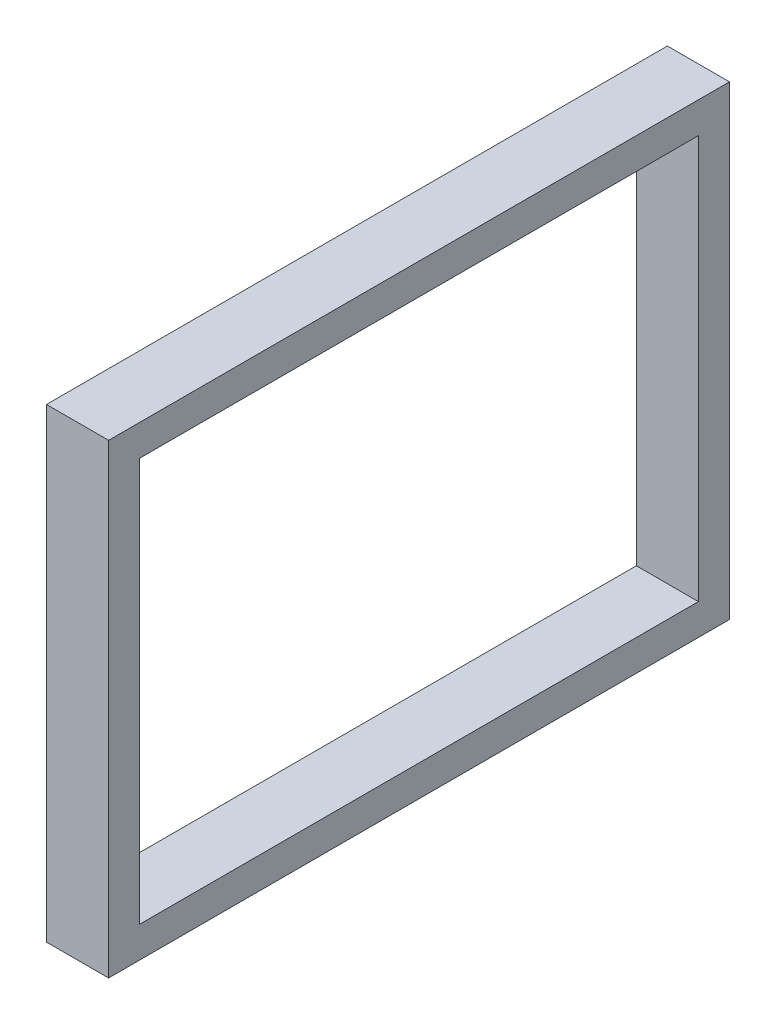
SolidWorks part; units mm, degrees
ref_plane "Front Plane" through (0, 0, 0) normal (0, 0, 1) x (1, 0, 0)
ref_plane "Top Plane" through (0, 0, 0) normal (0, 1, 0) x (1, 0, 0)
ref_plane "Right Plane" through (0, 0, 0) normal (1, 0, 0) x (0, 0, -1)
sketch "Sketch1" plane through (0, 0, 0) normal (1, 0, 0) x (0, 0, -1)
  line L0 (-270, 195) -> (270, 195)
  line L1 (-300, -225) -> (300, -225)
  line L2 (-300, -225) -> (-300, 225)
  line L3 (-300, 225) -> (300, 225)
  line L4 (300, -225) -> (300, 225)
  line L5 (-300, -225) -> (300, 225) construction
  line L6 (-300, 225) -> (300, -225) construction
  line L7 (270, -195) -> (270, 195)
  line L8 (-270, -195) -> (270, -195)
  line L9 (-270, -195) -> (-270, 195)
  point P0 (0, 0)
  dimension "D1" = 600
  dimension "D2" = 450
  dimension "D3" = 30
extrude "Boss-Extrude1" add sketch "Sketch1" along normal blind 60
